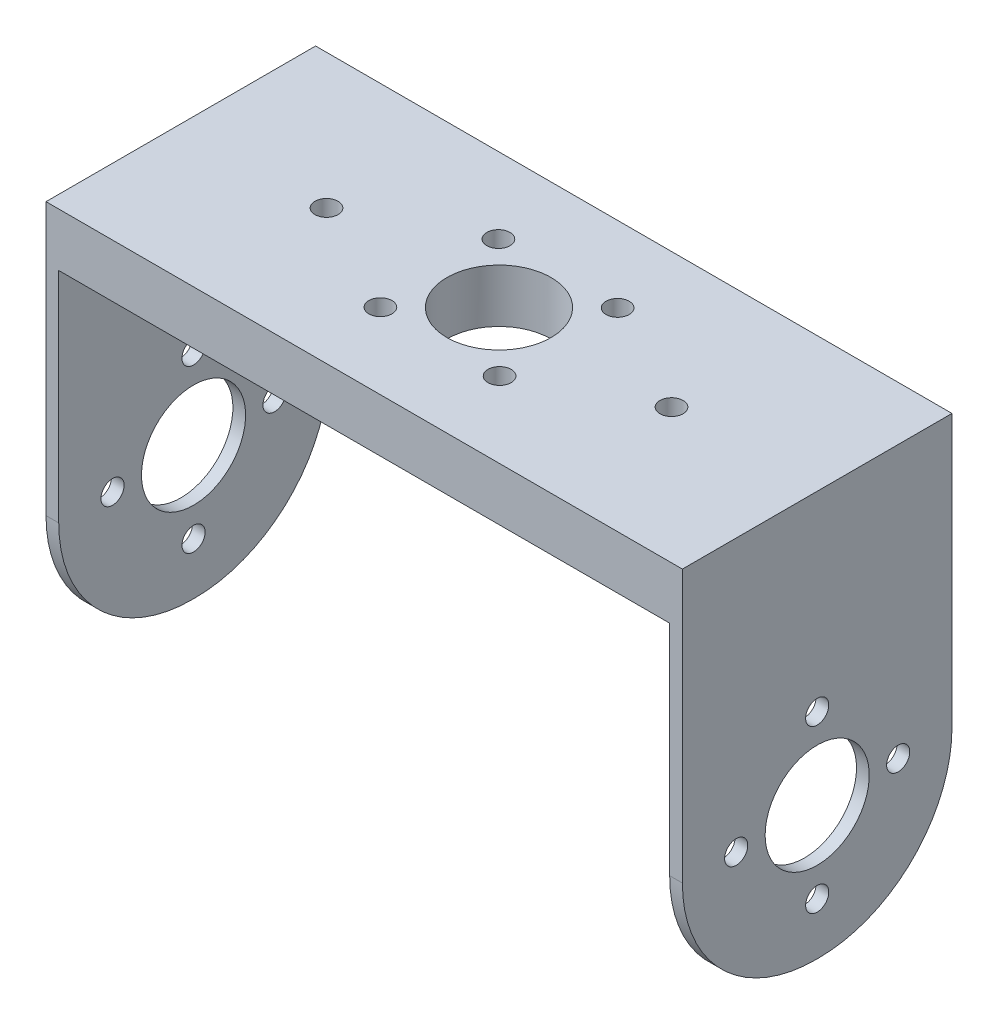
SolidWorks part; units mm, degrees
ref_plane "Front Plane" through (0, 0, 0) normal (0, 0, 1) x (1, 0, 0)
ref_plane "Top Plane" through (0, 0, 0) normal (0, 1, 0) x (1, 0, 0)
ref_plane "Right Plane" through (0, 0, 0) normal (1, 0, 0) x (0, 0, -1)
sketch "Sketch1" plane through (0, 0, 0) normal (0, 1, 0) x (1, 0, 0)
  line L1 (0, 0) -> (55, 0)
  line L2 (0, 0) -> (0, 23.3)
  line L3 (0, 23.3) -> (55, 23.3)
  line L4 (55, 0) -> (55, 23.3)
  dimension "D1" = 55
  dimension "D2" = 23.3
extrude "MountPlate" add sketch "Sketch1" along normal blind 4.6
sketch "Sketch3" plane through (0, 4.6, 0) normal (0, 1, 0) x (1, 0, 0)
  line L1 (55, 0) -> (55, 23.3) construction
  line L2 (55, 23.3) -> (0, 23.3) construction
  circle A0 centre (27.5, 11.65) radius 4.5
  point P6 (55, 11.65)
  point P7 (27.5, 23.3)
  dimension "D1" = 9
extrude "AxleHole-Mount" cut sketch "Sketch3" against normal up to surface (4.6 mm away) up to face at (27.5, 0, -11.65)
sketch "Sketch2" plane through (0, 4.6, 0) normal (0, 1, 0) x (1, 0, 0)
  line L0 (0, 23.3) -> (0, 0) construction
  circle A0 centre (22.35, 16.75) radius 1
  circle A1 centre (12.59, 11.65) radius 1
  circle A2 centre (32.65, 16.75) radius 1
  circle A3 centre (22.35, 6.55) radius 1
  circle A4 centre (42.41, 11.65) radius 1
  circle A5 centre (32.65, 6.55) radius 1
  circle A6 centre (27.5, 11.65) radius 4.5 construction
  point P17 (0, 11.65)
  dimension "D1" = 2
  dimension "D2" = 10.3
  dimension "D3" = 10.2
  dimension "D4" = 29.82
  dimension "D7" = 14.91
  dimension "D5" = 5.15
  dimension "D6" = 5.1
extrude "MountHoles" cut sketch "Sketch2" against normal up to surface (4.6 mm away) up to face at (27.5, 0, -16.15)
sketch "Sketch4" plane through (0, 0, 0) normal (0, -1, 0) x (1, 0, 0)
  line L0 (55, -23.3) -> (0, -23.3) construction
  line L1 (55, 0) -> (53.9, 0)
  line L2 (55, 0) -> (55, -23.3)
  line L3 (55, -23.3) -> (53.9, -23.3)
  line L4 (53.9, 0) -> (53.9, -23.3)
  line L6 (0, 0) -> (1.1, 0)
  line L7 (0, 0) -> (0, -23.3)
  line L8 (0, -23.3) -> (1.1, -23.3)
  line L9 (1.1, 0) -> (1.1, -23.3)
  dimension "D1" = 1.1
  dimension "D2" = 1.1
extrude "ServoLegs" add sketch "Sketch4" along normal blind 30.4
sketch "Sketch5" plane through (0, 0, 0) normal (-1, 0, 0) x (0, 0, 1)
  line L5 (0, -30.4) -> (-23.3, -30.4) construction
  circle A0 centre (-11.65, -18.9) radius 4.5
  point P2 (-11.65, -30.4)
  dimension "D1" = 9
  dimension "D2" = 11.5
extrude "CenterHoles" cut sketch "Sketch5" against normal up to surface (55 mm away) up to face at (55, -12.9, -11.65)
sketch "Sketch6" plane through (0, 0, 0) normal (-1, 0, 0) x (0, 0, 1)
  line L0 (0, -30.4) -> (-23.3, -30.4) construction
  circle A0 centre (-11.65, -25.9) radius 1
  circle A1 centre (-11.65, -18.9) radius 4.5 construction
  circle A2 centre (-18.65, -18.9) radius 1
  circle A3 centre (-11.65, -11.9) radius 1
  circle A4 centre (-4.65, -18.9) radius 1
  point P5 (-11.65, -30.4)
  point P16 (-11.65, -18.9)
  dimension "D1" = 2
  dimension "D2" = 7
  dimension "D3" = 4
extrude "Rotator-MountHoles" cut sketch "Sketch6" against normal up to surface (55 mm away) up to face at (55, -18.9, -7.15)
fillet "Fillet1" radius 11.5 1 edges at (0.55, -30.4, -23.3)
fillet "Fillet2" radius 11.5 1 edges at (0.55, -30.4, 0)
fillet "Fillet3" radius 11.5 1 edges at (54.45, -30.4, 0)
fillet "Fillet4" radius 11.5 1 edges at (54.45, -30.4, -23.3)
equation "\"D7@Sketch2\"=\"D4@Sketch2\"/2"
equation "\"D5@Sketch2\"=\"D2@Sketch2\"/2"
equation "\"D6@Sketch2\"=\"D3@Sketch2\"/2"
equation "\"D2@Sketch4\"=\"D1@Sketch4\""
equation "\"D1@ServoLegs\"=35-\"D1@MountPlate\""
equation "\"D2@Sketch5\"=7+\"D1@Sketch5\"/2"
